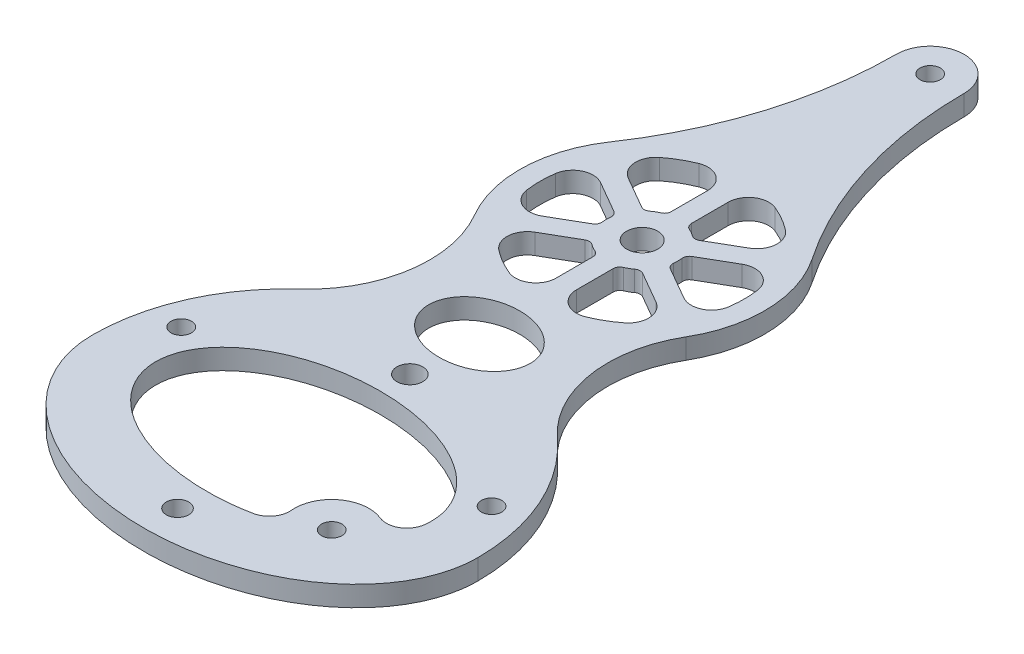
SolidWorks part; units mm, degrees
ref_plane "Front Plane" through (0, 0, 0) normal (0, 0, 1) x (1, 0, 0)
ref_plane "Top Plane" through (0, 0, 0) normal (0, 1, 0) x (1, 0, 0)
ref_plane "Right Plane" through (0, 0, 0) normal (1, 0, 0) x (0, 0, -1)
sketch "Sketch1" plane through (0, 0, 0) normal (0, 1, 0) x (1, 0, 0)
  line L0 (0, -1000) -> (0, 49000) construction
  arc A0 (-14.944, 10.1452) -> (-6.7076, 56.4182) centre (-62.5986, 42.4971) ccw construction
  arc A1 (-14.944, 10.1452) -> (-15.6012, -9.1024) centre (0, 0) ccw construction
  arc A2 (-19.0837, -31.5984) -> (-15.6012, -9.1024) centre (-31.2024, -18.2047) ccw construction
  arc A3 (-19.0837, -31.5984) -> (-28.4436, -52.6898) centre (0, -52.6898) ccw construction
  arc A4 (-14.944, 10.1452) -> (-6.7076, 56.4182) centre (-62.5986, 42.4971) ccw construction
  arc A5 (-14.944, 10.1452) -> (-15.6012, -9.1024) centre (0, 0) ccw
  arc A6 (-19.0837, -31.5984) -> (-15.6012, -9.1024) centre (-31.2024, -18.2047) ccw
  arc A7 (-19.0837, -31.5984) -> (-28.4436, -52.6898) centre (0, -52.6898) ccw
  arc A8 (-14.944, 10.1452) -> (-5, 42.4971) centre (-62.5986, 42.4971) ccw
  arc A9 (-5, 42.4971) -> (5, 42.4971) centre (0, 42.4971) cw
  arc A10 (14.944, 10.1452) -> (5, 42.4971) centre (62.5986, 42.4971) cw
  arc A11 (14.944, 10.1452) -> (15.6012, -9.1024) centre (0, 0) cw
  arc A12 (19.0837, -31.5984) -> (15.6012, -9.1024) centre (31.2024, -18.2047) cw
  arc A13 (19.0837, -31.5984) -> (28.4436, -52.6898) centre (0, -52.6898) cw
  circle A14 centre (22.8961, -45.1123) radius 1.5 construction
  circle A15 centre (-22.8961, -45.1123) radius 1.5 construction
  circle A16 centre (22.8961, -45.1123) radius 1.5
  circle A17 centre (-22.8961, -45.1123) radius 1.5
  circle A18 centre (0, 0) radius 2.3
  circle A19 centre (0, 42.4971) radius 1.5 construction
  circle A20 centre (0, 42.4971) radius 1.5
  circle A21 centre (0, -68.5564) radius 1.65 construction
  circle A22 centre (0, -34.2782) radius 1.9092 construction
  circle A23 centre (0, -68.5564) radius 1.65
  circle A24 centre (0, -34.2782) radius 1.9092
  circle A25 centre (0, 0) radius 2.3 construction
  ellipse E0 centre (0, -52.6898) end of major axis (-28.4436, -52.6898) minor radius 20.8666 (-28.4436, -52.6898) -> (28.4436, -52.6898) ccw construction
  ellipse E1 centre (0, -52.6898) end of major axis (-28.4436, -52.6898) minor radius 20.8666 (-28.4436, -52.6898) -> (28.4436, -52.6898) ccw
  ellipse E2 centre (0, -51.4173) end of major axis (20.3628, -51.4173) minor radius 12.813 construction
  ellipse E3 centre (0, -24.0072) end of major axis (-7.5, -24.0072) minor radius 5.9448 construction
  ellipse E4 centre (0, -51.4173) end of major axis (20.3628, -51.4173) minor radius 12.813
  ellipse E5 centre (0, -24.0072) end of major axis (-7.5, -24.0072) minor radius 5.9448
extrude "Boss-Extrude1" add sketch "Sketch1" along normal blind 3
sketch "Sketch2" plane through (0, 0, 0) normal (0, -1, 0) x (1, 0, 0)
  circle A0 centre (14.1202, 59.9265) radius 5.5
  circle A1 centre (14.1202, 59.9265) radius 8.2743 construction
  dimension "D1" = 11
extrude "Boss-Extrude2" add sketch "Sketch2" against normal up to surface (3 mm away) up to face at (0, 3, 70.2064)
fillet "Fillet1" radius 3 2 edges at (9.417, 1.5, 62.7778) (18.5629, 1.5, 56.6842)
sketch "Sketch3" plane through (0, 3, 0) normal (0, 1, 0) x (1, 0, 0)
  circle A0 centre (14.1202, -59.9265) radius 1.5
  circle A1 centre (14.1202, -59.9265) radius 5.5 construction
  circle A2 centre (-22.8961, -45.1123) radius 1.5 construction
extrude "Cut-Extrude1" cut sketch "Sketch3" against normal through all
sketch "Sketch4" plane through (0, 3, 0) normal (0, 1, 0) x (1, 0, 0)
  line L0 (-1.5, -5.0833) -> (-1.5, -14.9875)
  line L1 (-5.0906, -8.8172) -> (5.0906, -8.8172) construction
  line L2 (5.0906, -8.8172) -> (10.1812, 0) construction
  line L3 (10.1812, 0) -> (5.0906, 8.8172) construction
  line L4 (5.0906, 8.8172) -> (-5.0906, 8.8172) construction
  line L5 (-5.0906, 8.8172) -> (-10.1812, 0) construction
  line L6 (-10.1812, 0) -> (-5.0906, -8.8172) construction
  line L7 (0, -201000) -> (0, 249000) construction
  line L8 (0, 0) -> (-5.0906, -8.8172) construction
  line L9 (-3.6523, -3.8407) -> (-12.2296, -8.7928)
  circle A0 centre (0, 0) radius 8.8172 construction
  circle A1 centre (0, 0) radius 2.3 construction
  circle A2 centre (-5.0906, -8.8172) radius 7.8812 construction
  circle A3 centre (-5.0906, -8.8172) radius 4.8812 construction
  arc A4 (-1.5, -5.0833) -> (-3.6523, -3.8407) centre (0, 0) cw
  circle A5 centre (0, 0) radius 18.0624 construction
  arc A6 (-14.944, 10.1452) -> (-15.6012, -9.1024) centre (0, 0) ccw construction
  arc A7 (-1.5, -14.9875) -> (-12.2296, -8.7928) centre (0, 0) cw
  dimension "D2" = 1.5
  dimension "D1" = 3
extrude "Cut-Extrude2" cut sketch "Sketch4" against normal through all
fillet "Fillet2" radius 3 2 edges at (-1.5, 1.5, 14.9875) (-12.2296, 1.5, 8.7928)
fillet "Fillet3" radius 1 2 edges at (-1.5, 1.5, 5.0833) (-3.6523, 1.5, 3.8407)
pattern_circular "CirPattern1" count 6 over 360 about axis through (0, 0, 0) along (0, 1, 0) of "Fillet2", "Cut-Extrude2", "Fillet3"
